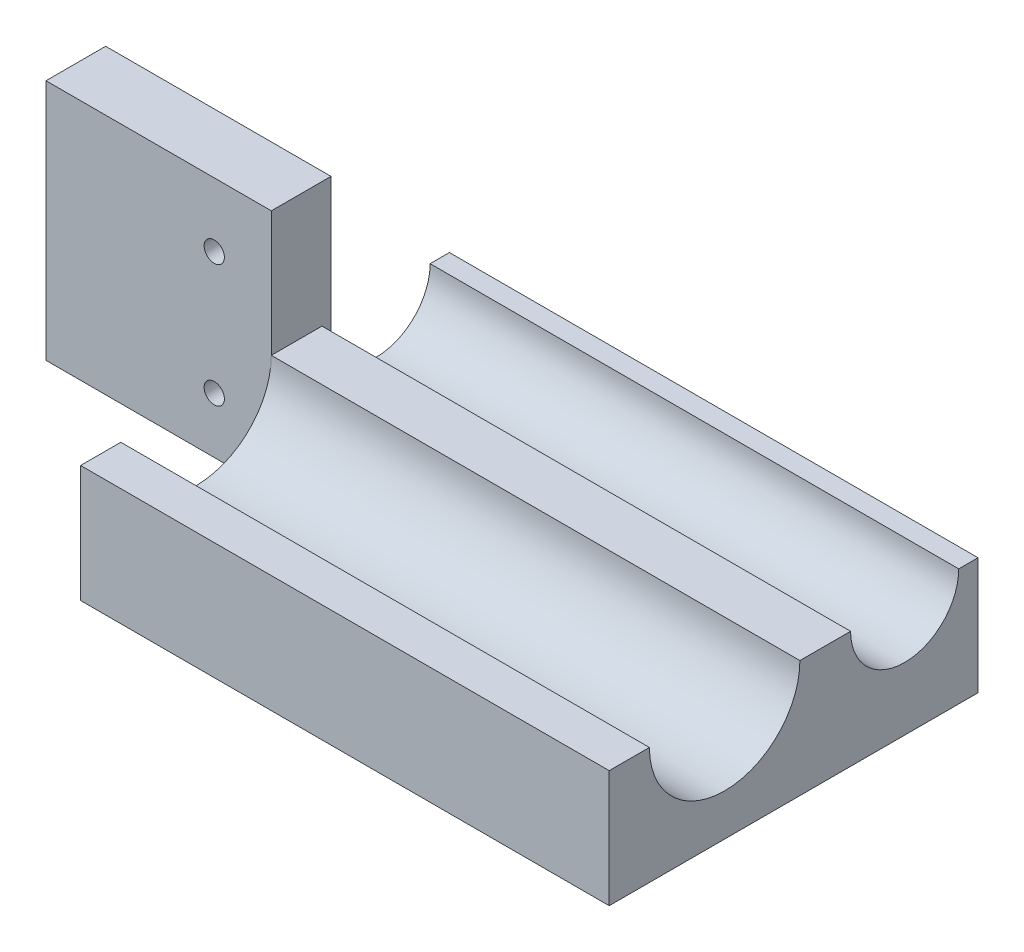
SolidWorks part; units mm, degrees
ref_plane "Front Plane" through (0, 0, 0) normal (0, 0, 1) x (1, 0, 0)
ref_plane "Top Plane" through (0, 0, 0) normal (0, 1, 0) x (1, 0, 0)
ref_plane "Right Plane" through (0, 0, 0) normal (1, 0, 0) x (0, 0, -1)
sketch "Sketch1" plane through (0, 0, 0) normal (1, 0, 0) x (0, 0, -1)
  line L0 (40.9201, 42.0261) -> (40.9201, 0) construction
  line L1 (0, 0) -> (81.8401, 0)
  line L2 (0, 0) -> (0, 25.9608)
  line L3 (81.8401, 0) -> (81.8401, 25.9608)
  line L4 (0, 25.9608) -> (8.92, 25.9608) construction
  line L6 (42.32, 25.9608) -> (53.5625, 25.9608) construction
  line L7 (42.32, 25.9608) -> (53.5625, 25.9608)
  line L8 (0, 25.9608) -> (8.92, 25.9608)
  line L10 (42.32, 25.9608) -> (53.5625, 25.9608)
  line L11 (77.5625, 25.9608) -> (81.8401, 25.9608)
  arc A0 (8.92, 25.9608) -> (42.32, 25.9608) centre (25.62, 25.9608) ccw
  arc A1 (53.5625, 25.9608) -> (77.5625, 25.9608) centre (65.5625, 25.9608) ccw
  circle A2 centre (40.9201, 21.013) radius 46 construction
  point P14 (0, 0)
  point P15 (65.5625, 25.9608)
  dimension "D1" = 92
  dimension "D3" = 12
  dimension "D4" = 16.7
  dimension "D2" = 39.9425
extrude "Boss-Extrude1" add sketch "Sketch1" along normal blind 117.3 contours L8 L2 L1 L3 L7
sketch "Sketch7" plane through (0, 0, 0) normal (-1, 0, 0) x (0, 0, 1)
  line L0 (0, 0) -> (-81.8401, 0) construction
  line L1 (-55.5625, 0) -> (-42.32, 0)
  line L2 (-55.5625, 0) -> (-55.5625, 53.7409)
  line L3 (-55.5625, 53.7409) -> (-42.32, 53.7409)
  line L4 (-42.32, 0) -> (-42.32, 53.7409)
  line L5 (-42.32, 25.9608) -> (-53.5625, 25.9608) construction
  line L6 (-42.32, 25.9608) -> (-53.5625, 25.9608) construction
  arc A0 (-77.5625, 25.9608) -> (-53.5625, 25.9608) centre (-65.5625, 25.9608) ccw construction
  arc A1 (-77.5625, 25.9608) -> (-53.5625, 25.9608) centre (-65.5625, 25.9608) ccw construction
  circle A2 centre (-65.5625, 25.9608) radius 6 construction
  point P9 (-51.8572, 42.0361)
  point P13 (-35.7032, 53.7409)
  dimension "D1" = 12
  dimension "D2" = 10
extrude "Boss-Extrude2" add sketch "Sketch7" along normal blind 50
sketch "Sketch8" plane through (0, 0, -55.5625) normal (0, 0, -1) x (-1, 0, 0)
  line L0 (50, 53.7409) -> (0, 53.7409) construction
  line L1 (0, 53.7409) -> (0, 19.3275) construction
  line L2 (50, 53.7409) -> (0, 53.7409) construction
  line L3 (0, 53.7409) -> (0, 19.3275) construction
  line L4 (3.5, 19.9608) -> (3.5, 31.9608) construction
  line L5 (3.5, 19.9608) -> (3.5, 31.9608) construction
  circle A0 centre (12.6639, 39.5608) radius 2.25
  circle A1 centre (12.6639, 12.3608) radius 2.25
  point P2 (0, 0)
  point P10 (3.5, 25.9608)
  point P11 (12.6639, 15.9228)
  dimension "D3" = 4.5
  dimension "D1" = 13.6
  dimension "D2" = 12.6639
  dimension "D4" = 13.6
extrude "Cut-Extrude1" cut sketch "Sketch8" against normal up to surface (13.2425 mm away) up to face at (-20, 26.6885, -42.32)
sketch "Sketch9" plane through (0, 0, -55.5625) normal (0, 0, -1) x (-1, 0, 0)
  circle A0 centre (12.6639, 39.5608) radius 5.25
  circle A1 centre (12.6639, 12.3608) radius 4.9302
  dimension "D1" = 10.5
extrude "Cut-Extrude2" cut sketch "Sketch9" against normal blind 4.5
equation "\"MotorDIA\"= 22'ME 405 Motor Diameter"
equation "\"SyringeDIA\"= 31.4'60ml Syringe Diameter"
equation "\"MotorShaftDIA\"= 6'Motor Shaft Dia"
equation "\"MotorKeyway\"= 1'ME 405 Motor Shaft Keyway Depth"
equation "\"MotorLength\"= 67.5'ME 405 Motor Length Excluding Shaft"
equation "\"SyringeLength\"= 117.3'60ml Syringe Length Excluding Nozzle"
equation "\"3Dtol\"= .5'Sizing Tolerance for 3D printed parts"
equation "\"ChamberDIA\"= 100 - 4'Buoyancy Chamber inner Diameter"
equation "\"ChamberThk\" = 2mm'Buoyancy Chamber Wall Thickness"
equation "\"D4@Sketch1\"=15.70mm+\"3Dtol\"*2"
equation "\"D3@Sketch1\"=11.00mm+\"3Dtol\"*2"
